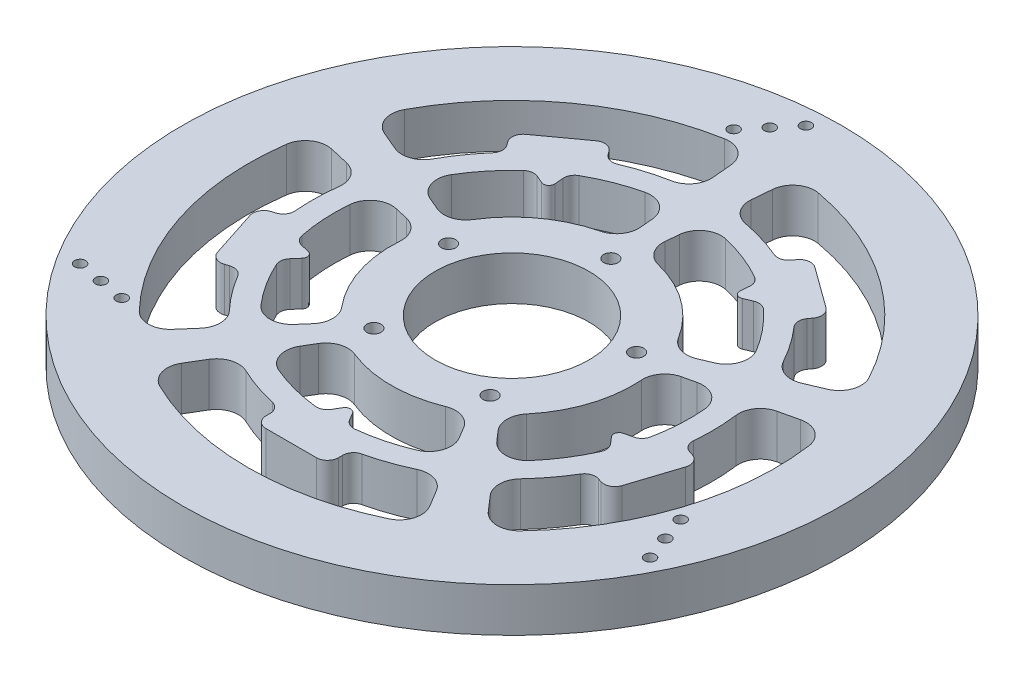
SolidWorks part; units mm, degrees
material "6061-T6 (SS)"
ref_plane "Front Plane" through (0, 0, 0) normal (0, 0, 1) x (1, 0, 0)
ref_plane "Top Plane" through (0, 0, 0) normal (0, 1, 0) x (1, 0, 0)
ref_plane "Right Plane" through (0, 0, 0) normal (1, 0, 0) x (0, 0, -1)
sketch "Sketch1" plane through (0, 0, 0) normal (0, 1, 0) x (1, 0, 0)
  circle A0 centre (0, 0) radius 150
  circle A1 centre (0, 0) radius 35
  point P5 (0, 0)
  point P6 (0, 0)
  dimension "D1" = 300
  dimension "D2" = 70
extrude "Boss-Extrude1" add sketch "Sketch1" along normal blind 20
sketch "Sketch2" plane through (0, 0, 0) normal (0, 1, 0) x (1, 0, 0)
  line L0 (0, 0) -> (0, 142) construction
  line L1 (-8, 141.7745) -> (-23.0151, 123.8802) construction
  circle A0 centre (0, 0) radius 142 construction
  circle A1 centre (0, 0) radius 134 construction
  circle A2 centre (0, 0) radius 126 construction
  circle A3 centre (-8, 141.7745) radius 2.5
  circle A4 centre (-15.5075, 132.8273) radius 2.5
  circle A5 centre (-23.0151, 123.8802) radius 2.5
  point P12 (0, 0)
  dimension "D1" = 284
  dimension "D2" = 268
  dimension "D3" = 252
  dimension "D6" = 5
  dimension "D4" = 40
  dimension "D5" = 8
sketch "Sketch3" plane through (0, 0, 0) normal (0, 1, 0) x (1, 0, 0)
  line L0 (-33.0789, -55.0526) -> (-36.2032, -60.2522)
  line L1 (36.2032, -60.2522) -> (33.0789, -55.0526)
  line L2 (41.7181, -69.4306) -> (-41.7181, -69.4306) construction
  line L3 (28.3271, -47.1442) -> (0, 0) construction
  line L4 (0, 0) -> (-28.3271, -47.1442) construction
  line L5 (-2.1429, -74.7124) -> (-4.1797, -78.1022)
  line L6 (4.1797, -78.1022) -> (2.1429, -74.7124)
  circle A0 centre (0, 0) radius 76 construction
  arc A1 (-20.7369, -50.941) -> (20.7369, -50.941) centre (0, 0) ccw
  arc A2 (-31.5233, -74.6142) -> (-9.0225, -80.4959) centre (0, 0) ccw
  arc A3 (9.0225, -80.4959) -> (31.5233, -74.6142) centre (0, 0) ccw
  arc A4 (-36.2032, -60.2522) -> (-31.5233, -74.6142) centre (-27.6315, -65.4026) ccw
  arc A5 (-20.7369, -50.941) -> (-33.0789, -55.0526) centre (-24.5072, -60.2029) ccw
  arc A6 (20.7369, -50.941) -> (33.0789, -55.0526) centre (24.5072, -60.2029) cw
  arc A7 (31.5233, -74.6142) -> (36.2032, -60.2522) centre (27.6315, -65.4026) ccw
  arc A8 (2.1429, -74.7124) -> (-2.1429, -74.7124) centre (0, -76) ccw
  arc A9 (4.1797, -78.1022) -> (9.0225, -80.4959) centre (8.4656, -75.527) ccw
  arc A10 (-4.1797, -78.1022) -> (-9.0225, -80.4959) centre (-8.4656, -75.527) cw
  point P0 (0, -69.4306)
  point P21 (0, 0)
  point P26 (4.4774, -80.7926)
  point P28 (-2.3295, -75.0228)
  point P30 (5.7961, -80.7924)
  dimension "D1" = 152
  dimension "D2" = 55
  dimension "D3" = 81
  dimension "D5" = 10
  dimension "D6" = 5
  dimension "D7" = 5
  dimension "D4" = 62
sketch "Sketch4" plane through (0, 0, 0) normal (0, 1, 0) x (1, 0, 0)
  line L0 (-16.5, -95.5) -> (-16.5, -93.5615)
  line L1 (36.2032, -60.2522) -> (33.0789, -55.0526) construction
  line L2 (-33.0789, -55.0526) -> (-36.2032, -60.2522) construction
  line L3 (-11.5, -100.5) -> (11.5, -100.5)
  line L4 (36.2032, -60.2522) -> (33.0789, -55.0526)
  line L5 (-33.0789, -55.0526) -> (-36.2032, -60.2522)
  line L6 (-51.7632, -86.1485) -> (-56.4196, -93.898)
  line L7 (56.4196, -93.898) -> (51.7632, -86.1485)
  line L8 (16.5, -95.5) -> (16.5, -93.5615)
  arc A0 (20.3802, -88.6885) -> (38.9152, -82.2594) centre (0, 0) ccw
  arc A2 (-52.1977, -108.0527) -> (52.1977, -108.0527) centre (0, 0) ccw
  arc A3 (-38.9152, -82.2594) -> (-20.3802, -88.6885) centre (0, 0) ccw
  arc A4 (16.5, -93.5615) -> (20.3802, -88.6885) centre (21.5, -93.5615) cw
  arc A5 (11.5, -100.5) -> (16.5, -95.5) centre (11.5, -95.5) ccw
  arc A6 (-11.5, -100.5) -> (-16.5, -95.5) centre (-11.5, -95.5) cw
  arc A7 (-16.5, -93.5615) -> (-20.3802, -88.6885) centre (-21.5, -93.5615) ccw
  arc A8 (51.7632, -86.1485) -> (38.9152, -82.2594) centre (43.1916, -91.2989) ccw
  arc A9 (52.1977, -108.0527) -> (56.4196, -93.898) centre (47.8479, -99.0484) ccw
  arc A10 (-51.7632, -86.1485) -> (-38.9152, -82.2594) centre (-43.1916, -91.2989) cw
  arc A11 (-56.4196, -93.898) -> (-52.1977, -108.0527) centre (-47.8479, -99.0484) ccw
  point P3 (0, -100.5)
  point P13 (0, 23.1501)
  point P20 (16.5, -100.5)
  point P23 (-16.5, -100.5)
  point P28 (46.8685, -78.0022)
  point P33 (-46.8685, -78.0022)
  dimension "D1" = 91
  dimension "D2" = 120
  dimension "D5" = 5
  dimension "D6" = 10
  dimension "D3" = 100.5
  dimension "D4" = 33
sketch "Sketch5" plane through (0, 0, 0) normal (0, 1, 0) x (1, 0, 0)
  line L0 (0, 0) -> (0, 142) construction
  line L1 (0, 0) -> (0, 142) construction
  circle A1 centre (0, 0) radius 45 construction
  circle A2 centre (0, 45) radius 3.25
  point P5 (0, 0)
  point P10 (0, 0)
  dimension "D1" = 90
  dimension "D2" = 6.5
extrude "Cut-Extrude6" cut sketch "Sketch2" along normal blind 20 and the other way through all contours A4 | A5 | A3
pattern_circular "CirPattern1" count 3 every 120 about axis through (0, 0, 0) along (0, 1, 0) of "Cut-Extrude6"
extrude "Cut-Extrude8" cut sketch "Sketch3" along normal blind 20
extrude "Cut-Extrude9" cut sketch "Sketch4" along normal blind 20 contours L6 A11 A2 A9 L7 A8 A0 A4 L8 A5 L3 A6 L0 A7 A3 A10
extrude "Cut-Extrude10" cut sketch "Sketch5" along normal blind 20
pattern_circular "CirPattern2" count 5 every 72 about axis through (0, 0, 0) along (0, 1, 0) of "Cut-Extrude9", "Cut-Extrude8", "Cut-Extrude10"
